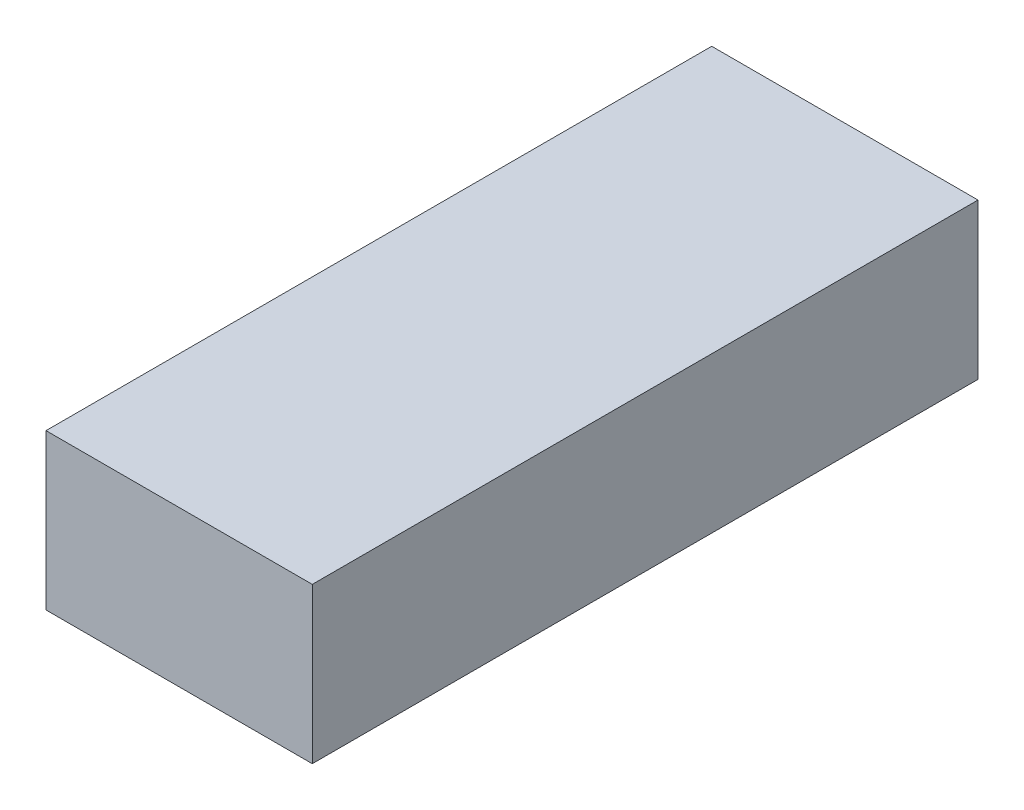
SolidWorks part; units mm, degrees
ref_plane "Front Plane" through (0, 0, 0) normal (0, 0, 1) x (1, 0, 0)
ref_plane "Top Plane" through (0, 0, 0) normal (0, 1, 0) x (1, 0, 0)
ref_plane "Right Plane" through (0, 0, 0) normal (1, 0, 0) x (0, 0, -1)
sketch "Sketch1" plane through (0, 0, 0) normal (0, 0, 1) x (1, 0, 0)
  line L1 (152.4, -88.9) -> (-152.4, -88.9)
  line L2 (152.4, -88.9) -> (152.4, 88.9)
  line L3 (152.4, 88.9) -> (-152.4, 88.9)
  line L4 (-152.4, -88.9) -> (-152.4, 88.9)
  line L5 (152.4, -88.9) -> (-152.4, 88.9) construction
  line L6 (152.4, 88.9) -> (-152.4, -88.9) construction
  point P0 (0, 0)
  dimension "D1" = 177.8
  dimension "D2" = 304.8
extrude "Boss-Extrude1" add sketch "Sketch1" along normal blind 762
